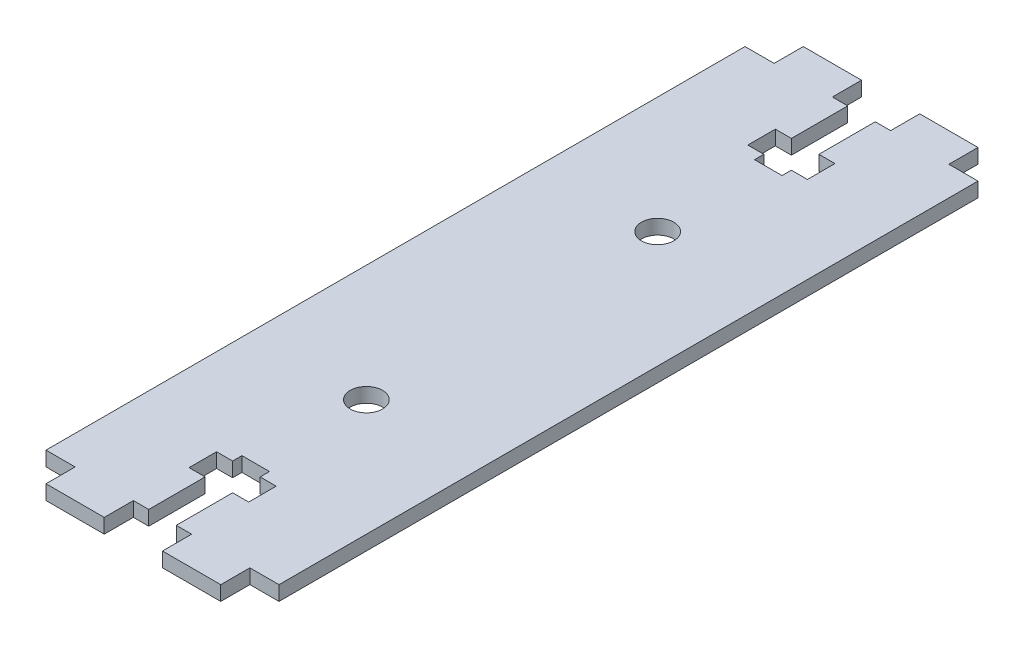
SolidWorks part; units mm, degrees
ref_plane "Front Plane" through (0, 0, 0) normal (0, 0, 1) x (1, 0, 0)
ref_plane "Top Plane" through (0, 0, 0) normal (0, 1, 0) x (1, 0, 0)
ref_plane "Right Plane" through (0, 0, 0) normal (1, 0, 0) x (0, 0, -1)
sketch "Sketch1" plane through (0, 0, 0) normal (0, 1, 0) x (1, 0, 0)
  line L0 (12.7, 0) -> (12.7, 76.2) construction
  line L1 (0, 0) -> (25.4, 0)
  line L2 (0, 0) -> (0, 76.2)
  line L3 (0, 76.2) -> (25.4, 76.2)
  line L4 (25.4, 0) -> (25.4, 76.2)
  line L5 (15.875, 76.2) -> (15.875, 79.375)
  line L6 (3.175, 76.2) -> (9.525, 76.2)
  line L7 (3.175, 76.2) -> (3.175, 79.375)
  line L8 (3.175, 79.375) -> (9.525, 79.375)
  line L9 (9.525, 76.2) -> (9.525, 79.375)
  line L10 (22.225, 79.375) -> (15.875, 79.375)
  line L11 (22.225, 76.2) -> (22.225, 79.375)
  line L12 (22.225, 76.2) -> (15.875, 76.2)
  line L13 (0, 38.1) -> (25.4, 38.1) construction
  line L14 (14.2, 66.04) -> (11.2, 66.04)
  line L15 (14.2, 66.04) -> (14.2, 76.2)
  line L16 (14.2, 76.2) -> (11.2, 76.2)
  line L17 (11.2, 66.04) -> (11.2, 76.2)
  line L18 (14.2, 66.04) -> (11.2, 76.2) construction
  line L19 (14.2, 76.2) -> (11.2, 66.04) construction
  line L20 (9.45, 67.056) -> (15.95, 67.056)
  line L21 (9.45, 67.056) -> (9.45, 70.056)
  line L22 (9.45, 70.056) -> (15.95, 70.056)
  line L23 (15.95, 67.056) -> (15.95, 70.056)
  line L24 (9.45, 67.056) -> (15.95, 70.056) construction
  line L25 (9.45, 70.056) -> (15.95, 67.056) construction
  line L26 (9.45, 6.144) -> (15.95, 9.144) construction
  line L27 (9.45, 9.144) -> (15.95, 6.144) construction
  line L28 (14.2, 0) -> (11.2, 10.16) construction
  line L29 (14.2, 10.16) -> (11.2, 0) construction
  line L30 (15.95, 9.144) -> (15.95, 6.144)
  line L31 (9.45, 6.144) -> (15.95, 6.144)
  line L32 (9.45, 9.144) -> (9.45, 6.144)
  line L33 (9.45, 9.144) -> (15.95, 9.144)
  line L34 (11.2, 10.16) -> (11.2, 0)
  line L35 (14.2, 0) -> (11.2, 0)
  line L36 (14.2, 10.16) -> (14.2, 0)
  line L37 (14.2, 10.16) -> (11.2, 10.16)
  line L38 (22.225, 0) -> (15.875, 0)
  line L39 (22.225, 0) -> (22.225, -3.175)
  line L40 (22.225, -3.175) -> (15.875, -3.175)
  line L41 (9.525, 0) -> (9.525, -3.175)
  line L42 (3.175, -3.175) -> (9.525, -3.175)
  line L43 (3.175, 0) -> (3.175, -3.175)
  line L44 (3.175, 0) -> (9.525, 0)
  line L45 (15.875, 0) -> (15.875, -3.175)
  point P15 (12.7, 71.12)
  point P20 (12.7, 68.556)
  point P43 (12.7, 7.644)
  point P44 (12.7, 5.08)
  dimension "D1" = 76.2
  dimension "D2" = 25.4
  dimension "D3" = 3.175
  dimension "D4" = 6.35
  dimension "D5" = 19.05
  dimension "D6" = 3
  dimension "D7" = 6.5
  dimension "D8" = 10.16
  dimension "D9" = 3
  dimension "D10" = 1.016
extrude "Boss-Extrude1" add sketch "Sketch1" along normal blind 1.5875 contours L37 L36 L33 L30 L31 L1 L4 L3 L15 L22 L23 L20 L14 L17 L21 L2 L34 L32 | L3 L9 L8 L7 | L3 L11 L10 L5 | L1 L43 L42 L41 | L1 L45 L40 L39
sketch "Sketch2" plane through (0, 1.5875, 0) normal (0, 1, 0) x (1, 0, 0)
  line L0 (0, 38.1) -> (25.4, 38.1) construction
  line L1 (0, 0) -> (0, 76.2) construction
  line L2 (25.4, 0) -> (25.4, 76.2) construction
  line L3 (12.7, 66.04) -> (12.7, 10.16) construction
  line L4 (14.2, 66.04) -> (11.2, 66.04) construction
  line L5 (14.2, 10.16) -> (11.2, 10.16) construction
  circle A0 centre (12.7, 53.975) radius 1.764
  circle A1 centre (12.7, 22.225) radius 1.764
  dimension "D1" = 3.5281
  dimension "D2" = 31.75
extrude "Cut-Extrude1" cut sketch "Sketch2" against normal blind 1.5875
